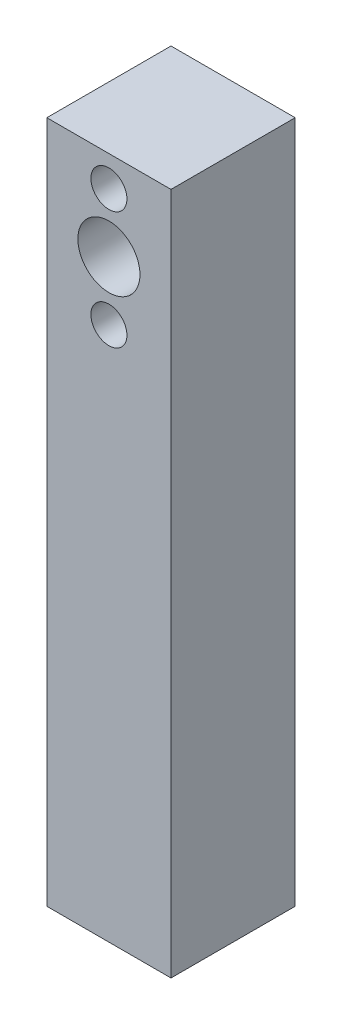
SolidWorks part; units mm, degrees
ref_plane "Front Plane" through (0, 0, 0) normal (0, 0, 1) x (1, 0, 0)
ref_plane "Top Plane" through (0, 0, 0) normal (0, 1, 0) x (1, 0, 0)
ref_plane "Right Plane" through (0, 0, 0) normal (1, 0, 0) x (0, 0, -1)
sketch "Sketch1" plane through (0, 0, 0) normal (0, 0, 1) x (1, 0, 0)
  line L1 (0, 0) -> (12.7, 0)
  line L2 (0, 0) -> (0, 69.85)
  line L3 (0, 69.85) -> (12.7, 69.85)
  line L4 (12.7, 0) -> (12.7, 69.85)
  dimension "D1" = 69.85
  dimension "D2" = 12.7
extrude "Boss-Extrude1" add sketch "Sketch1" along normal blind 12.7
sketch "Sketch2" plane through (0, 0, 12.7) normal (0, 0, 1) x (1, 0, 0)
  line L0 (0, 0) -> (12.7, 0) construction
  line L1 (0, 60.706) -> (6.35, 60.706) construction
  line L2 (0, 69.85) -> (0, 0) construction
  line L3 (6.35, 60.706) -> (12.7, 60.706) construction
  line L4 (12.7, 0) -> (12.7, 69.85) construction
  line L5 (6.35, 60.706) -> (6.35, 66.7385) construction
  line L6 (6.35, 60.706) -> (6.35, 54.6735) construction
  circle A0 centre (6.35, 60.706) radius 3.175
  circle A1 centre (6.35, 66.7385) radius 1.8415
  circle A2 centre (6.35, 54.6735) radius 1.8415
  dimension "D1" = 6.35
  dimension "D4" = 3.683
  dimension "D2" = 60.706
  dimension "D3" = 6.0325
extrude "Cut-Extrude1" cut sketch "Sketch2" against normal through all
